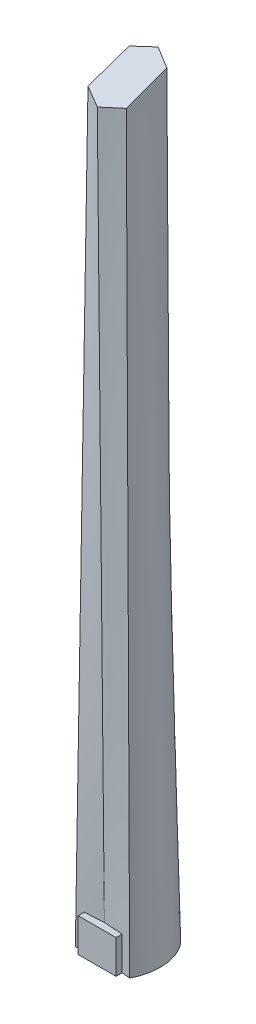
SolidWorks part; units mm, degrees
ref_plane "Front Plane" through (0, 0, 0) normal (0, 0, 1) x (1, 0, 0)
ref_plane "Top Plane" through (0, 0, 0) normal (0, 1, 0) x (1, 0, 0)
ref_plane "Right Plane" through (0, 0, 0) normal (1, 0, 0) x (0, 0, -1)
sketch "Sketch3" plane through (0, 0, 0) normal (1, 0, 0) x (0, 0, -1)
  line L1 (18.2, 3.1) -> (23.7, 3.1)
  line L2 (18.2, 3.1) -> (18.2, -3.1)
  line L3 (18.2, -3.1) -> (23.7, -3.1)
  line L4 (23.7, 3.1) -> (23.7, -3.1) construction
  arc A0 (23.7, 3.1) -> (23.7, -3.1) centre (23.7, 0) cw
  point P5 (18.2, 0)
  dimension "D2" = 5.5
  dimension "D1" = 6.2
extrude "Boss-Extrude3" add sketch "Sketch3" along normal mid plane 7
ref_plane "Plane1" through (0, 138.1, 0) normal (0, 1, 0) x (1, 0, 0)
sketch "Sketch4" plane through (0, 138.1, 0) normal (0, 1, 0) x (1, 0, 0)
  line L0 (-3.5, 27.575) -> (-3.5, 20.075)
  line L7 (-3.5, 20.075) -> (0, 18.2)
  line L8 (0, 18.2) -> (3.5, 20.075)
  line L9 (-3.5, 27.575) -> (0, 29.45)
  line L10 (0, 29.45) -> (3.5, 27.575)
  line L11 (3.5, 27.575) -> (3.5, 20.075)
  line L12 (3.5, 27.575) -> (-3.5, 27.575) construction
  point P7 (0, 27.575)
  dimension "D1" = 7
  dimension "D2" = 11.25
  dimension "D3" = 7.5
sketch "Sketch5" plane through (0, -3.1, 0) normal (0, -1, 0) x (1, 0, 0)
  line L3 (5.0111, -19.2) -> (0, -19.6039)
  line L4 (0, -19.6039) -> (-5.0111, -19.2)
  line L7 (0.5, -31.4741) -> (0, -31.6)
  line L8 (0, -31.6) -> (-0.5, -31.4741)
  ellipse E0 centre (0, -23.7) end of major axis (0, -31.5) minor radius 6.135 (-5.0111, -19.2) -> (-0.5, -31.4741) ccw
  ellipse E1 centre (0, -23.7) end of major axis (0, -31.5) minor radius 6.135 (0.5, -31.4741) -> (5.0111, -19.2) ccw
  dimension "D1" = 12.27
  dimension "D2" = 7.8
  dimension "D4" = 4.0961
  dimension "D5" = 0.1
  dimension "D6" = 1
loft "Loft4" add profiles "Sketch5", "Sketch4"
sketch "Sketch6" plane through (0, 0, 0) normal (1, 0, 0) x (0, 0, -1)
  line L0 (29.45, 138.1) -> (18.2398, 134.1)
  line L1 (18.2398, 134.1) -> (18.2, 138.1)
  line L2 (19.5422, 3.1) -> (18.2, 138.1) construction
  line L3 (18.2, 138.1) -> (29.45, 138.1)
  dimension "D1" = 4
extrude "Cut-Extrude1" cut sketch "Sketch6" against normal mid plane 10
hole_wizard "M6 Tapped Hole1" [suppressed] positions "Sketch7" profile "Sketch8" tap size "M6" standard "ISO"
sketch "Sketch7" plane through (0, 0, 0) normal (0, 0, 1) x (1, 0, 0)
  point P0 (0, 0)
sketch "Sketch8" plane through (0, 0, 0) normal (1, 0, 0) x (0, -1, 0)
  line L0 (0, 0) -> (0, 7.5022)
  line L1 (0, 7.5022) -> (2.5, 6)
  line L2 (2.5, 6) -> (2.5, 0)
  line L5 (2.5, 0) -> (0, 0)
  line L10 (0, 7.5022) -> (-2.5, 6) construction
  line L11 (0, -6.35) -> (0, 107.95) construction
  dimension "Tap Drill Dia." = 5
  dimension "Tap Drill Depth" = 6
  dimension "Drill Angle" = 118
cosmetic thread "Hole Thread1" [suppressed] parameters "D1"=6, "D2"=6
sketch "Sketch9" [suppressed] plane through (0, 0, 0) normal (0, 0, 1) x (1, 0, 0)
  line L0 (-0.2181, 4.9952) -> (0, 4.8693)
  line L1 (0, 4.8693) -> (0.2181, 4.9952)
  line L2 (0.2181, 4.9952) -> (0, 0) construction
  line L3 (0, 0) -> (-0.2181, 4.9952) construction
  circle A0 centre (0, 0) radius 5 construction
  arc A1 (-0.2181, 4.9952) -> (0.2181, 4.9952) centre (0, 0) cw
  dimension "D1" = 5
  dimension "D2" = 120
extrude "Cut-Extrude2" [suppressed] cut sketch "Sketch9" against normal up to next
pattern_circular "CirPattern1" [suppressed] count 72 over 360
